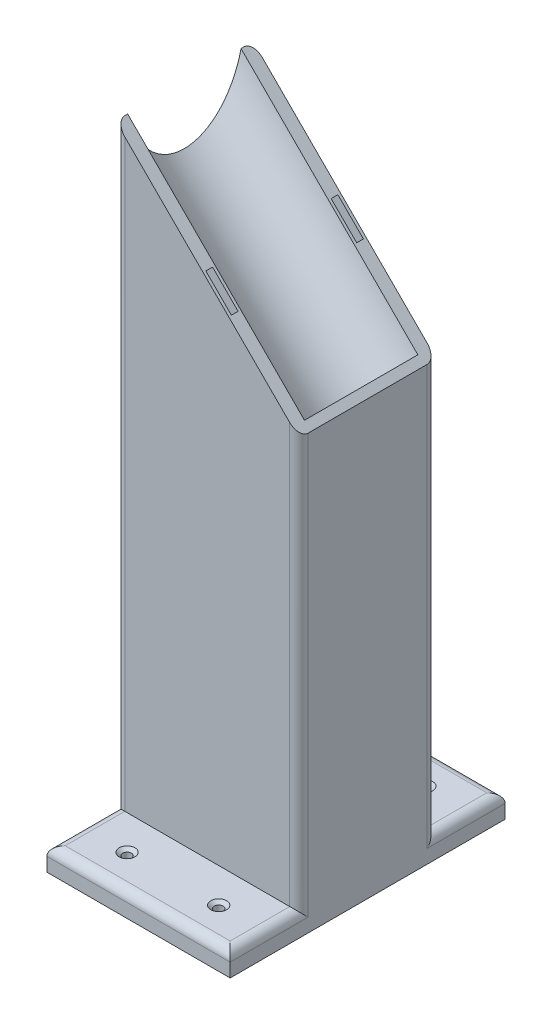
SolidWorks part; units mm, degrees
ref_plane "Front Plane" through (0, 0, 0) normal (0, 0, 1) x (1, 0, 0)
ref_plane "Top Plane" through (0, 0, 0) normal (0, 1, 0) x (1, 0, 0)
ref_plane "Right Plane" through (0, 0, 0) normal (1, 0, 0) x (0, 0, -1)
sketch "Sketch1" plane through (0, 0, 0) normal (0, 1, 0) x (1, 0, 0)
  line L1 (-106.7955, -38.1) -> (-157.5955, -38.1)
  line L2 (-106.7955, -38.1) -> (-106.7955, 38.1)
  line L3 (-106.7955, 38.1) -> (-157.5955, 38.1)
  line L4 (-157.5955, -38.1) -> (-157.5955, 38.1)
  line L5 (-106.7955, -38.1) -> (-157.5955, 38.1) construction
  line L6 (-106.7955, 38.1) -> (-157.5955, -38.1) construction
  point P0 (-132.1955, 0)
  dimension "D1" = 50.8
  dimension "D2" = 76.2
extrude "Boss-Extrude1" add sketch "Sketch1" along normal blind 6.35
sketch "Sketch2" plane through (0, 6.35, 0) normal (0, 1, 0) x (1, 0, 0)
  line L0 (-157.5955, 38.1) -> (-157.5955, -38.1) construction
  line L1 (-106.7955, -19.05) -> (-157.5955, -19.05)
  line L2 (-106.7955, -19.05) -> (-106.7955, 19.05)
  line L3 (-106.7955, 19.05) -> (-157.5955, 19.05)
  line L4 (-157.5955, -19.05) -> (-157.5955, 19.05)
  line L5 (-106.7955, -19.05) -> (-157.5955, 19.05) construction
  line L6 (-106.7955, 19.05) -> (-157.5955, -19.05) construction
  line L8 (-106.7955, -38.1) -> (-106.7955, 38.1) construction
  point P0 (-132.1955, 0)
  dimension "D1" = 38.1
extrude "Boss-Extrude2" add sketch "Sketch2" along normal blind 171.6066
sketch "Sketch5" plane through (0, 0, 19.05) normal (0, 0, 1) x (1, 0, 0)
  line L0 (-144.8955, 157.8906) -> (-118.328, 131.3231)
  line L1 (-144.8955, 157.8906) -> (-144.8955, 108.1657) construction
  line L2 (-157.5955, 177.9566) -> (-106.7955, 177.9566) construction
  dimension "D1" = 45
  dimension "D2" = 20.066
sketch "Sketch18" plane through (0, 0, -19.05) normal (0, 0, -1) x (-1, 0, 0)
  line L0 (157.5955, 177.9566) -> (157.5955, 155.4814) construction
  line L1 (157.5955, 177.9566) -> (157.5955, 6.35) construction
  line L2 (157.5955, 177.9566) -> (184.1058, 151.4463) construction
  dimension "D1" = 45
ref_plane "Plane1" through (-167.776, 167.776, 0) normal (0.7071, -0.7071, 0) x (-0.7071, -0.7071, 0)
sketch "Sketch19" plane through (-167.776, 167.776, 0) normal (0.7071, -0.7071, 0) x (-0.7071, -0.7071, 0)
  line L0 (16.3468, 0) -> (-14.3975, 0) construction
  line L1 (-14.3975, 16.51) -> (-14.3975, -16.51)
  line L2 (-14.3975, 19.05) -> (-14.3975, -49.2738) construction
  arc A0 (-14.3975, -16.51) -> (-14.3975, 16.51) centre (-14.3975, 0) ccw
  dimension "D1" = 33.02
extrude "Cut-Extrude1" cut sketch "Sketch19" against normal through all and the other way through all
ref_plane "Plane2" through (6.5885, 6.5885, 0) normal (-0.7071, -0.7071, 0) x (0, 0, 1)
other "SurfaceCut1"
sketch "Sketch20" plane through (6.5885, 6.5885, 0) normal (0.7071, 0.7071, 0) x (0, 0, -1)
  line L0 (19.05, 232.1911) -> (19.05, 160.3491) construction
  line L1 (-19.05, 160.3491) -> (19.05, 160.3491)
  line L2 (-19.05, 160.3491) -> (-19.05, 162.8891)
  line L3 (-19.05, 162.8891) -> (19.05, 162.8891)
  line L4 (19.05, 160.3491) -> (19.05, 162.8891)
  dimension "D1" = 2.54
extrude "Boss-Extrude3" add sketch "Sketch20" against normal up to surface up to face at (-132.1955, 141.3313, 3.9273)
sketch "Sketch22" plane through (-113.3839, 113.3839, 0) normal (0.7071, -0.7071, 0) x (0, 0, -1)
  line L0 (-15.709, 9.3175) -> (15.709, 9.3175)
  line L1 (-18.1618, 9.3175) -> (18.1618, 9.3175) construction
  arc A0 (-15.709, 9.3175) -> (15.709, 9.3175) centre (0, 14.3975) ccw construction
  arc A1 (-15.709, 9.3175) -> (15.709, 9.3175) centre (0, 14.3975) ccw construction
  arc A2 (15.709, 9.3175) -> (-15.709, 9.3175) centre (0, 9.3175) cw
extrude "Boss-Extrude4" add sketch "Sketch22" along normal up to surface up to face at (-106.7955, 60.2748, 1.905)
sketch "Sketch23" plane through (0, 6.35, 0) normal (0, 1, 0) x (1, 0, 0)
  line L0 (-106.7955, 28.575) -> (-157.5955, 28.575) construction
  line L1 (-106.7955, 19.05) -> (-106.7955, 38.1) construction
  line L2 (-157.5955, 38.1) -> (-157.5955, 19.05) construction
  line L3 (-132.1955, 38.1) -> (-132.1955, -38.1) construction
  line L4 (-106.7955, 38.1) -> (-157.5955, 38.1) construction
  line L5 (-157.5955, -38.1) -> (-106.7955, -38.1) construction
  line L6 (-106.7955, -28.575) -> (-157.5955, -28.575) construction
  line L7 (-106.7955, -38.1) -> (-106.7955, -19.05) construction
  line L8 (-157.5955, -19.05) -> (-157.5955, -38.1) construction
  line L9 (-144.8955, -19.05) -> (-144.8955, -38.1) construction
  line L10 (-157.5955, -19.05) -> (-106.7955, -19.05) construction
  line L11 (-119.4955, -19.05) -> (-119.4955, -38.1) construction
  line L12 (-157.5955, -38.1) -> (-144.8955, -38.1)
  dimension "D1" = 12.7
  dimension "D2" = 12.7
hole_wizard "CSK for #2 Flat Head Machine Screw (100)1" positions "Sketch26" profile "Sketch25" countersink size "#2" standard "ANSI Inch" end condition through all
sketch "Sketch26" plane through (0, 6.35, 0) normal (0, 1, 0) x (1, 0, 0)
  line L0 (-106.7955, -28.575) -> (-157.5955, -28.575) construction
  line L1 (-144.8955, -19.05) -> (-144.8955, -38.1) construction
  line L2 (-119.4955, -19.05) -> (-119.4955, -38.1) construction
  point P0 (-144.8955, -28.575)
  point P2 (-119.4955, -28.575)
sketch "Sketch25" plane through (-144.8955, 6.35, 28.575) normal (1, 0, 0) x (0, 0, 1)
  line L0 (0, 0) -> (0, 6.35)
  line L1 (0, 6.35) -> (1.2192, 6.35)
  line L2 (1.2192, 6.35) -> (1.2192, 0.8099)
  line L3 (1.2192, 0.8099) -> (2.1844, 0)
  line L5 (2.1844, 0) -> (0, 0)
  line L6 (-1.2192, 0.8099) -> (-2.1844, 0) construction
  line L11 (0, -6.35) -> (0, 107.95) construction
  dimension "Thru Hole Dia." = 2.4384
  dimension "Thru Hole Depth" = 6.35
  dimension "Near C'Sink Dia." = 4.3688
  dimension "Near C'Sink Angle" = 100
mirror "Mirror1" about plane through (0, 0, 0) normal (0, 0, 1) of "CSK for #2 Flat Head Machine Screw (100)1"
fillet "Fillet1" radius 2.54 4 edges
fillet "Fillet2" radius 2.54 6 edges at (-132.1955, 6.35, -38.1) (-132.1955, 6.35, 38.1)
sketch "Sketch27" plane through (-106.7955, 0, 0) normal (1, 0, 0) x (0, 0, -1)
  line L0 (-240.3842, 123.9915) -> (-35.0509, 123.9915) construction
sketch "Sketch29" plane through (6.5885, 6.5885, 0) normal (0.7071, 0.7071, 0) x (0, 0, -1)
  line L3 (-16.4356, 197.8891) -> (-18.2964, 187.8891) construction
  line L4 (16.4356, 187.8891) -> (18.2964, 187.8891)
  line L6 (15.709, 162.8891) -> (-15.709, 162.8891) construction
  line L7 (0, 162.8891) -> (0, 234.7248) construction
  line L8 (16.4356, 187.8891) -> (16.4356, 197.8891)
  line L9 (16.4356, 197.8891) -> (18.2964, 197.8891)
  line L10 (18.2964, 187.8891) -> (18.2964, 197.8891)
  line L11 (16.4356, 187.8891) -> (18.2964, 197.8891) construction
  line L12 (16.4356, 197.8891) -> (18.2964, 187.8891) construction
  line L13 (-16.4356, 187.8891) -> (-18.2964, 197.8891) construction
  line L14 (-18.2964, 187.8891) -> (-18.2964, 197.8891)
  line L15 (-16.4356, 197.8891) -> (-18.2964, 197.8891)
  line L16 (-16.4356, 187.8891) -> (-16.4356, 197.8891)
  line L17 (-16.4356, 187.8891) -> (-18.2964, 187.8891)
  point P4 (17.366, 192.8891)
  point P14 (-17.366, 192.8891)
  dimension "D1" = 25
  dimension "D2" = 10
extrude "Cut-Extrude2" cut sketch "Sketch29" against normal blind 30
sketch "Sketch30" plane through (0, 6.35, 0) normal (0, 1, 0) x (1, 0, 0)
  line L0 (-155.0555, 12.709) -> (-155.0555, -12.709)
  line L1 (-155.0555, 12.709) -> (-111.5915, 12.709)
  line L2 (-155.0555, -12.709) -> (-111.5915, -12.709)
  line L3 (-111.5915, 12.709) -> (-111.5915, -12.709)
  line L4 (-108.5915, 15.709) -> (-157.5955, 15.709) construction
  line L5 (-157.5955, 15.709) -> (-157.5955, -15.709) construction
  line L6 (-108.5915, 15.709) -> (-108.5915, -15.709) construction
  line L7 (-157.5955, -15.709) -> (-108.5915, -15.709) construction
  dimension "D1" = 3
  dimension "D2" = 2.54
  dimension "D3" = 3
  dimension "D4" = 3
extrude "Cut-Extrude3" cut sketch "Sketch30" along normal offset from surface (148.1324 mm away) 3
